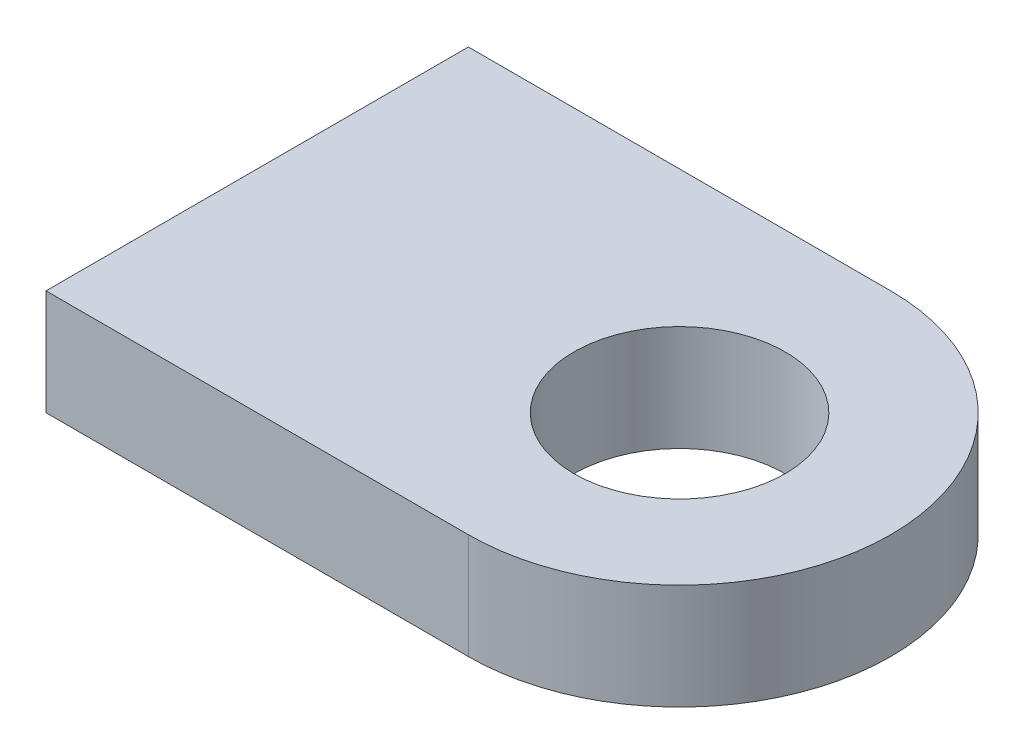
SolidWorks part; units mm, degrees
ref_plane "Front Plane" through (0, 0, 0) normal (0, 0, 1) x (1, 0, 0)
ref_plane "Top Plane" through (0, 0, 0) normal (0, 1, 0) x (1, 0, 0)
ref_plane "Right Plane" through (0, 0, 0) normal (1, 0, 0) x (0, 0, -1)
sketch "Sketch1" plane through (0, 0, 0) normal (0, 1, 0) x (1, 0, 0)
  line L0 (0, -10) -> (0, 10)
  line L1 (0, 10) -> (20, 10)
  line L2 (0, -10) -> (20, -10)
  arc A0 (20, 10) -> (20, -10) centre (20, 0) cw
  circle A1 centre (20, 0) radius 5
  point P4 (0, 0)
  dimension "D4" = 10
  dimension "D5" = 10
  dimension "D1" = 20
  dimension "D2" = 20
  dimension "D3" = 20
extrude "Boss-Extrude1" add sketch "Sketch1" along normal blind 5
